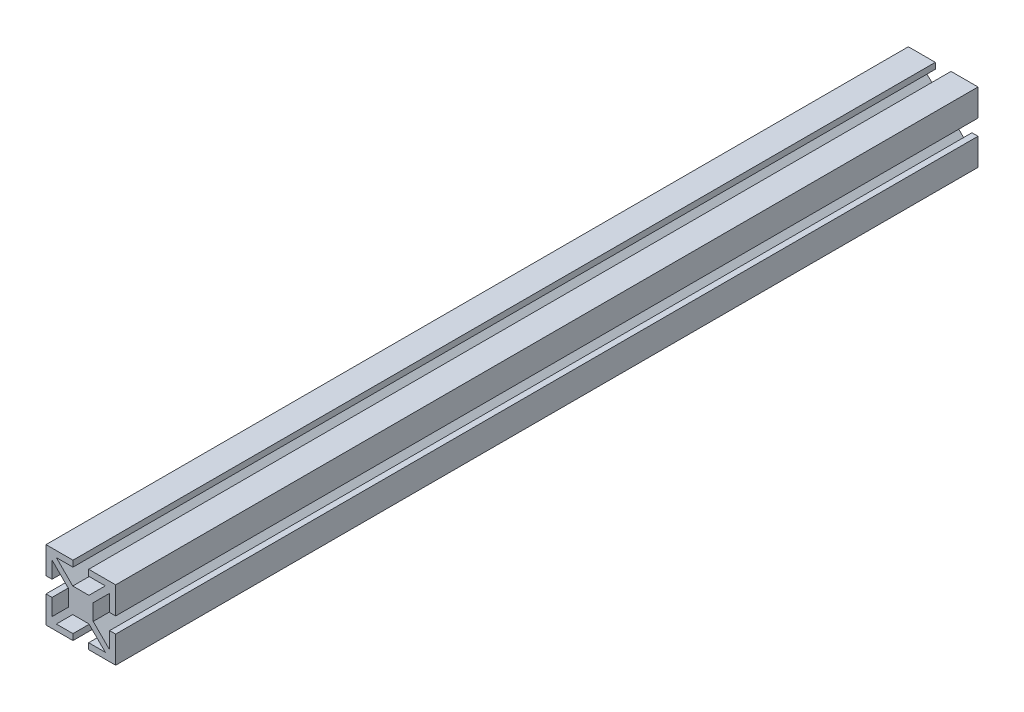
SolidWorks part; units mm, degrees
ref_plane "Front Plane" through (0, 0, 0) normal (0, 0, 1) x (1, 0, 0)
ref_plane "Top Plane" through (0, 0, 0) normal (0, 1, 0) x (1, 0, 0)
ref_plane "Right Plane" through (0, 0, 0) normal (1, 0, 0) x (0, 0, -1)
sketch "Sketch1" plane through (11.365, -9.8462, 0) normal (0, 0, 1) x (1, 0, 0)
  line L0 (-11.365, 9.8462) -> (-11.365, 32.3924) construction
  line L1 (-11.365, 9.8462) -> (-35.43, 9.8462) construction
  line L2 (-11.365, 9.8462) -> (-7.5972, 6.0784) construction
  line L3 (-24.065, 22.5462) -> (-14.2298, 22.5462)
  line L4 (-14.2298, 22.5462) -> (-14.2298, 20.3364)
  line L5 (-14.2298, 20.3364) -> (-20.2926, 20.3364)
  line L6 (-20.2926, 20.3364) -> (-14.3109, 14.3547)
  line L7 (-14.3109, 14.3547) -> (-8.4191, 14.3547)
  line L8 (-15.8735, 12.7921) -> (-15.8735, 6.9003)
  line L9 (-21.8552, 18.7738) -> (-15.8735, 12.7921)
  line L10 (-21.8552, 12.711) -> (-21.8552, 18.7738)
  line L11 (-24.065, 12.711) -> (-21.8552, 12.711)
  line L12 (-24.065, 22.5462) -> (-24.065, 12.711)
  line L13 (-14.3109, 5.3377) -> (-8.4191, 5.3377)
  line L14 (-20.2926, -0.644) -> (-14.3109, 5.3377)
  line L15 (-21.8552, 0.9186) -> (-15.8735, 6.9003)
  line L16 (-21.8552, 6.9814) -> (-21.8552, 0.9186)
  line L17 (-24.065, 6.9814) -> (-21.8552, 6.9814)
  line L18 (-24.065, -2.8538) -> (-24.065, 6.9814)
  line L19 (-14.2298, -0.644) -> (-20.2926, -0.644)
  line L20 (-14.2298, -2.8538) -> (-14.2298, -0.644)
  line L21 (-24.065, -2.8538) -> (-14.2298, -2.8538)
  line L22 (1.335, -2.8538) -> (-8.5002, -2.8538)
  line L23 (-8.5002, -2.8538) -> (-8.5002, -0.644)
  line L24 (-8.5002, -0.644) -> (-2.4374, -0.644)
  line L25 (1.335, -2.8538) -> (1.335, 6.9814)
  line L26 (1.335, 6.9814) -> (-0.8748, 6.9814)
  line L27 (-0.8748, 6.9814) -> (-0.8748, 0.9186)
  line L28 (-0.8748, 0.9186) -> (-6.8565, 6.9003)
  line L29 (-2.4374, -0.644) -> (-8.4191, 5.3377)
  line L30 (1.335, 22.5462) -> (1.335, 12.711)
  line L31 (1.335, 12.711) -> (-0.8748, 12.711)
  line L32 (-0.8748, 12.711) -> (-0.8748, 18.7738)
  line L33 (-0.8748, 18.7738) -> (-6.8565, 12.7921)
  line L34 (-6.8565, 12.7921) -> (-6.8565, 6.9003)
  line L35 (-2.4374, 20.3364) -> (-8.4191, 14.3547)
  line L36 (-8.5002, 20.3364) -> (-2.4374, 20.3364)
  line L37 (-8.5002, 22.5462) -> (-8.5002, 20.3364)
  line L38 (1.335, 22.5462) -> (-8.5002, 22.5462)
  point P20 (-15.8735, 9.8462)
  point P26 (-6.8565, 9.8462)
  point P36 (-11.365, 5.3377)
  point P42 (-11.365, 14.3547)
  dimension "D1" = 9.8352
  dimension "D2" = 12.7
  dimension "D3" = 4.5085
  dimension "D4" = 2.2098
  dimension "D5" = 1.1049
extrude "Boss-Extrude1" add sketch "Sketch1" along normal blind 314.452
other "1010<1>"
